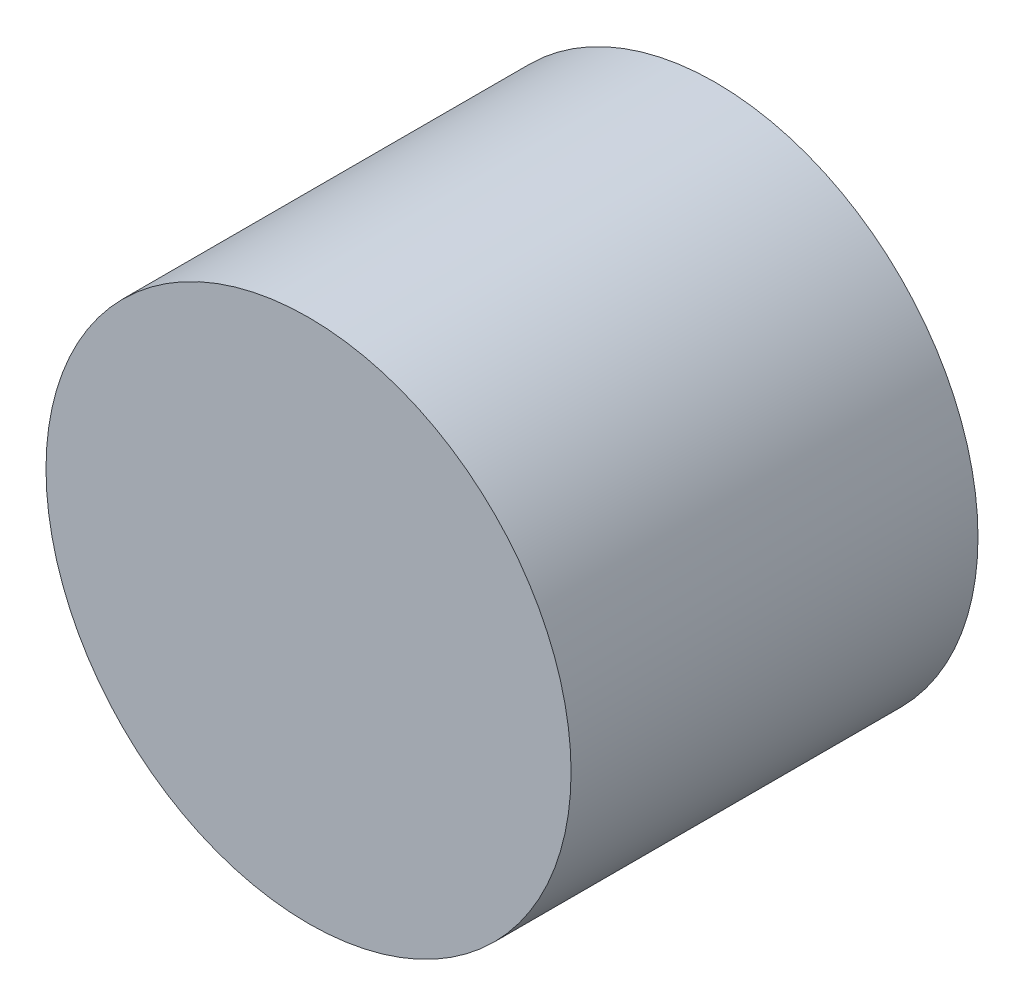
SolidWorks part; units mm, degrees
ref_plane "정면" through (0, 0, 0) normal (0, 0, 1) x (1, 0, 0)
ref_plane "윗면" through (0, 0, 0) normal (0, 1, 0) x (1, 0, 0)
ref_plane "우측면" through (0, 0, 0) normal (1, 0, 0) x (0, 0, -1)
sketch "스케치1" plane through (0, 0, 0) normal (0, 0, 1) x (1, 0, 0)
  circle A0 centre (0, 0) radius 60
  circle A1 centre (0, 0) radius 57
  dimension "D1" = 120
  dimension "D2" = 114
extrude "보스-돌출1" add sketch "스케치1" along normal blind 90
sketch "스케치2" plane through (0, 0, 90) normal (0, 0, 1) x (1, 0, 0)
  circle A0 centre (0, 0) radius 60
extrude "보스-돌출2" add sketch "스케치2" along normal blind 3
